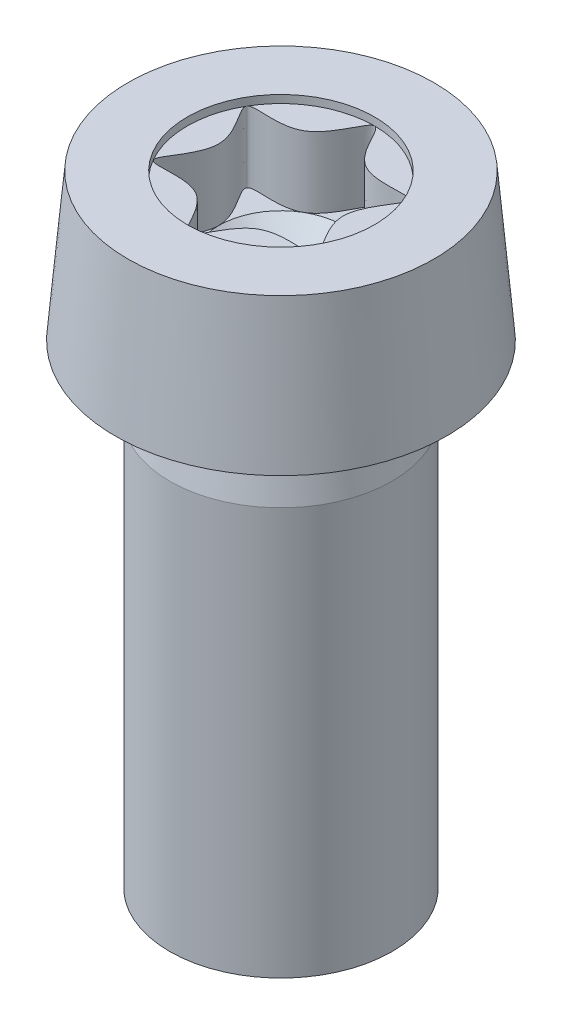
SolidWorks part; units mm, degrees
ref_plane "Front" through (0, 0, 0) normal (0, 0, 1) x (1, 0, 0)
ref_plane "Top" through (0, 0, 0) normal (0, 1, 0) x (1, 0, 0)
ref_plane "Right" through (0, 0, 0) normal (1, 0, 0) x (0, 0, -1)
other "Configuration Table"
sketch "Sketch1" plane through (0, 0, 0) normal (0, 0, 1) x (1, 0, 0)
  line L0 (0, 0) -> (0, 5.1006) construction
  line L1 (0, 13.1) -> (3.2288, 13.1)
  line L2 (3.2288, 13.1) -> (3.5, 10)
  line L3 (3.5, 10) -> (2.35, 10)
  line L4 (2.35, 0) -> (2.35, 8.6)
  line L5 (2.35, 0) -> (0, 0)
  line L6 (0, 0) -> (0, 13.1)
  line L7 (3.5, 10) -> (3.5, 9.3) construction
  line L8 (2.35, 8.6) -> (2.07, 10)
  line L9 (2.07, 10) -> (2.35, 10)
  line L10 (3.5, 9.3) -> (3.5, 0.7) construction
  dimension "length" = 10
  dimension "head_ht" = 3.1
  dimension "head_dia" = 7
  dimension "dia" = 4.7
  dimension "D1" = 5
  dimension "pitch" = 0.7
  dimension "thread_gap" = 1.4
  dimension "D2" = 0.28
  dimension "thread_length" = 8.6
revolve "Body-Revolve" add sketch "Sketch1" angle 360 about L0
cosmetic thread "ThreadCosmetic" [suppressed] parameters "D1"=8.6, "D2"=3.9423
fillet "Fillet1" radius 0.2 1 edges at (0, 10, -2.07)
sketch "Sketch2" plane through (0, 13.1, 0) normal (0, 1, 0) x (-1, 0, 0)
  line L0 (0, -2.1725) -> (0, 0)
  line L1 (0, 0) -> (-0.9875, -1.7104)
  circle A0 centre (0, 0) radius 1.975
  circle A1 centre (0, 0) radius 1.3167
  spline S0 degree 3 poles (0.426, -0.7378) (0, -2.5936) (-0.426, -0.7378) (-2.2461, -1.2968) (-0.8519, 0) (-2.2461, 1.2968) (-0.426, 0.7378) (0, 2.5936) (0.426, 0.7378) (2.2461, 1.2968) (0.8519, 0) (2.2461, -1.2968) (0.426, -0.7378) (0, -2.5936) (-0.426, -0.7378) knots -0.25 -0.166667 -0.083333 0 0.083333 0.166667 0.25 0.333333 0.416667 0.5 0.583333 0.666667 0.75 0.833333 0.916667 1 1.083333 1.166667 1.25 only from (0, -1.975) to (0, -1.975)
  point P5 (0, -1.975)
  point P7 (-0.6583, -1.1403)
  point P10 (-1.7104, -0.9875)
  point P11 (-1.7104, 0.9875)
  point P12 (0, 1.975)
  point P13 (1.7104, 0.9875)
  point P14 (1.7104, -0.9875)
  point P15 (-1.3167, 0)
  point P16 (-0.6583, 1.1403)
  point P17 (0.6583, 1.1403)
  point P18 (1.3167, 0)
  point P19 (0.6583, -1.1403)
  dimension "socket_dia" = 3.95
  dimension "D1" = 2.6333
  dimension "D2" = 2.1725
  dimension "D3" = 30
extrude "Socket-Cut-Extrude1" cut sketch "Sketch2" against normal blind 1.66 contours S0
sketch "Sketch3" plane through (0, 13.1, 0) normal (0, 1, 0) x (-1, 0, 0)
  circle A0 centre (0, 0) radius 1.975
  dimension "D1" = 3.95
extrude "Socket-Cut-Extrude2" cut sketch "Sketch3" against normal blind 0.166
sketch "Sketch4" plane through (0, 0, 0) normal (0, 0, 1) x (1, 0, 0)
  line L0 (0, 11.44) -> (1.3167, 11.44)
  line L1 (1.7178, 11.44) -> (-1.7178, 11.44) construction
  line L2 (1.3167, 11.44) -> (0, 10.31)
  line L3 (0, 0) -> (0, 5.1006) construction
  line L4 (0, 10.31) -> (0, 11.44)
  line L5 (1.975, 13.1) -> (-1.975, 13.1) construction
  dimension "D1" = 2.79
  dimension "D2" = 1.3167
revolve "Drill-Cut-Revolve" cut sketch "Sketch4" angle 360 about axis through (0, 0, 0) along (0, 1, 0)
sketch "Sketch5" plane through (0, 0, 0) normal (0, 0, 1) x (1, 0, 0)
  line L0 (2.35, 0) -> (1.9711, 0.2187)
  line L1 (1.9711, 0.2187) -> (2.35, 0.4375)
  line L2 (2.35, 0) -> (2.35, 8.6) construction
  line L3 (2.35, 0.4375) -> (2.35, 0)
  line L4 (0, 0) -> (0, 5.1006) construction
  dimension "D1" = 1.9711
revolve "ThreadSchematic" [suppressed] cut sketch "Sketch5" angle 360 about axis through (0, 0, 0) along (0, 1, 0)
pattern_linear "ThdSchPat" [suppressed] count 12 spacing 0.7 along (0, 1, 0)
equation "\"D2@Sketch1\" = 0.2*\"thread_gap@Sketch1\""
equation "\"D1@Sketch2\" = \"socket_dia@Sketch2\" / 1.5"
equation "\"D2@Sketch2\" = \"socket_dia@Sketch2\" / 2 * 1.1"
equation "\"D1@Sketch3\" =\"socket_dia@Sketch2\""
equation "\"D1@Socket-Cut-Extrude2\" = .1 * \"socket_dep@Socket-Cut-Extrude1\""
equation "\"D1@Sketch4\" = 0.9*\"head_ht@Sketch1\""
equation "\"D2@Sketch4\" = \"D1@Sketch2\" / 2"
equation "\"D1@ThreadCosmetic\" = \"thread_length@Sketch1\""
equation "\"D2@ThreadCosmetic\" = \"dia@Sketch1\" - 1.0825 * \"pitch@Sketch1\""
equation "\"D1@Sketch5\" = \"D2@ThreadCosmetic\" / 2"
equation "\"D3@ThdSchPat\" = \"pitch@Sketch1\""
equation "\"D1@ThdSchPat\" = \"thread_length@Sketch1\" / \"pitch@Sketch1\""
